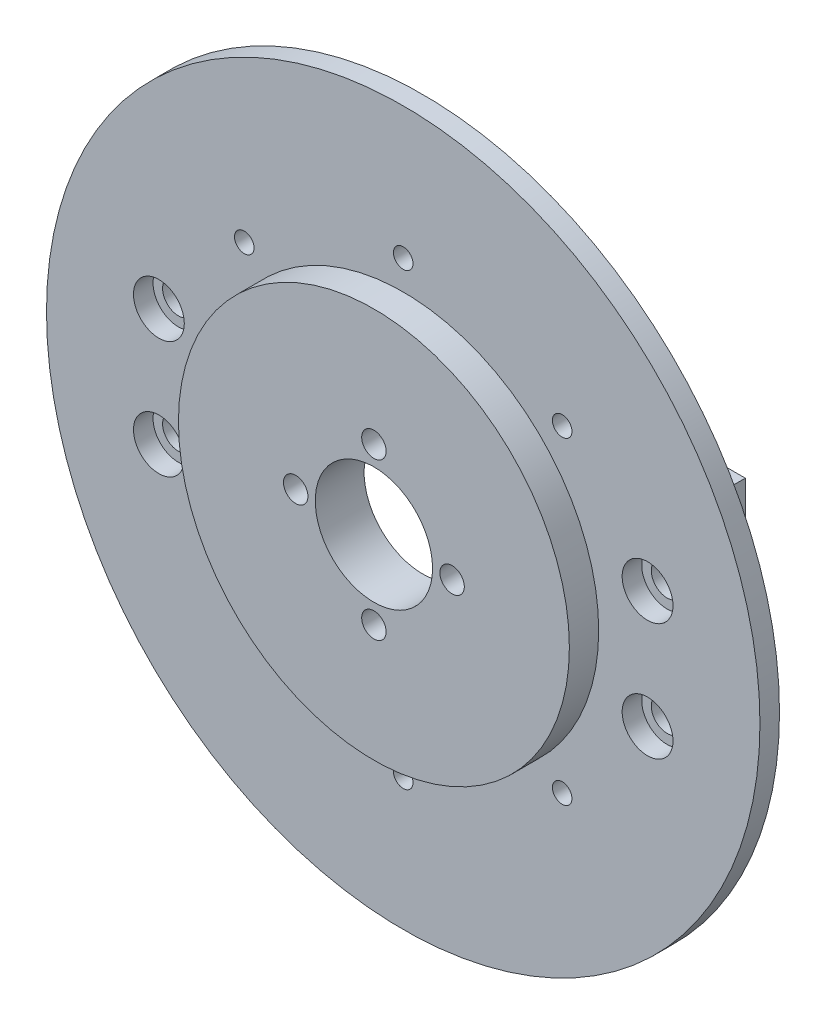
SolidWorks part; units mm, degrees
ref_plane "前视基准面" through (0, 0, 0) normal (0, 0, 1) x (1, 0, 0)
ref_plane "上视基准面" through (0, 0, 0) normal (0, 1, 0) x (1, 0, 0)
ref_plane "右视基准面" through (0, 0, 0) normal (1, 0, 0) x (0, 0, -1)
sketch "草图1" plane through (0, 0, 0) normal (0, 0, 1) x (1, 0, 0)
  line L1 (-74.8943, 22.0842) -> (-14.8943, 22.0842)
  line L2 (-74.8943, 22.0842) -> (-74.8943, -9.9158)
  line L3 (-74.8943, -9.9158) -> (-14.8943, -9.9158)
  line L4 (-14.8943, 22.0842) -> (-14.8943, -9.9158)
  dimension "D1" = 60
  dimension "D2" = 32
extrude "凸台-拉伸1" add sketch "草图1" along normal blind 3
sketch "草图3" plane through (0, 0, 3) normal (0, 0, 1) x (1, 0, 0)
  line L0 (-74.8943, 6.0842) -> (-14.8943, 6.0842) construction
  line L1 (-74.8943, 22.0842) -> (-74.8943, -9.9158) construction
  line L2 (-14.8943, -9.9158) -> (-14.8943, 22.0842) construction
  line L3 (-44.8943, 22.0842) -> (-44.8943, -9.9158) construction
  line L4 (-14.8943, 22.0842) -> (-74.8943, 22.0842) construction
  line L5 (-74.8943, -9.9158) -> (-14.8943, -9.9158) construction
  circle A0 centre (-44.8943, 6.0842) radius 36.5
  point P12 (-44.8943, 6.0842)
extrude "凸台-拉伸2" add sketch "草图3" along normal blind 2
sketch "草图4" plane through (0, 0, 5) normal (0, 0, 1) x (1, 0, 0)
  circle A0 centre (-44.8943, 29.0842) radius 1
  circle A2 centre (-44.8943, 6.0842) radius 36.5 construction
  dimension "D1" = 2
  dimension "D2" = 0
  dimension "D3" = 23
extrude "切除-拉伸2" cut sketch "草图4" against normal blind 10
pattern_circular "阵列(圆周)1" count 8 over 360 about axis through (-44.8943, 6.0842, 0) along (0, 0, 1) of "切除-拉伸2"
sketch "草图5" plane through (0, 0, 0) normal (0, 0, -1) x (-1, 0, 0)
  circle A0 centre (28.6308, 22.3477) radius 5
  circle A1 centre (61.1577, 22.3477) radius 5
  circle A2 centre (28.6308, -10.1792) radius 5
  circle A3 centre (61.1577, -10.1792) radius 5
extrude "切除-拉伸3" cut sketch "草图5" against normal blind 3
sketch "草图6" plane through (0, 0, 0) normal (0, 0, -1) x (-1, 0, 0)
  circle A0 centre (21.8943, 6.0842) radius 3
  circle A1 centre (67.8943, 6.0842) radius 3
extrude "凸台-拉伸3" add sketch "草图6" against normal blind 5
sketch "草图7" plane through (0, 0, 0) normal (0, 0, -1) x (-1, 0, 0)
  line L0 (14.8943, -9.9158) -> (14.8943, 22.0842) construction
  line L1 (14.8943, 22.0842) -> (23.6378, 22.0842) construction
  line L2 (23.6378, -9.9158) -> (14.8943, -9.9158) construction
  line L3 (66.1508, 22.0842) -> (74.8943, 22.0842) construction
  circle A0 centre (19.8943, 12.0842) radius 1.62
  circle A1 centre (19.8943, 0.0842) radius 1.62
  circle A2 centre (69.8943, 12.0842) radius 1.62
  circle A3 centre (69.8943, 0.0842) radius 1.62
  dimension "D1" = 3.24
  dimension "D2" = 5
  dimension "D3" = 10
  dimension "D4" = 3.24
  dimension "D5" = 10
  dimension "D6" = 5
  dimension "D7" = 3.24
  dimension "D8" = 50
  dimension "D9" = 10
  dimension "D10" = 3.24
  dimension "D11" = 0
  dimension "D12" = 50
extrude "切除-拉伸4" cut sketch "草图7" against normal blind 5
sketch "草图9" plane through (0, 0, 5) normal (0, 0, 1) x (1, 0, 0)
  circle A0 centre (-69.8943, 12.0842) radius 2.6
  circle A1 centre (-69.8943, 0.0842) radius 2.6
  circle A2 centre (-19.8943, 12.0842) radius 2.6
  circle A3 centre (-19.8943, 0.0842) radius 2.6
extrude "切除-拉伸5" cut sketch "草图9" against normal blind 2
sketch "草图10" plane through (0, 0, 5) normal (0, 0, 1) x (1, 0, 0)
  circle A0 centre (-44.8943, 6.0842) radius 20
extrude "凸台-拉伸4" add sketch "草图10" along normal blind 3
sketch "草图11" plane through (0, 0, 8) normal (0, 0, 1) x (1, 0, 0)
  circle A0 centre (-44.8943, 14.0842) radius 1.25
  circle A1 centre (-44.8943, 6.0842) radius 20 construction
  circle A2 centre (-44.8943, 6.0842) radius 20 construction
  dimension "D1" = 0
  dimension "D2" = 8
extrude "切除-拉伸6" cut sketch "草图11" against normal blind 10
pattern_circular "阵列(圆周)2" count 4 over 360 about axis through (-44.8943, 6.0842, 0) along (0, 0, 1) of "切除-拉伸6"
sketch "草图12" plane through (0, 0, 0) normal (0, 0, -1) x (-1, 0, 0)
  line L1 (23.6378, 22.0842) -> (66.1508, 22.0842)
  line L2 (23.6378, 22.0842) -> (23.6378, -9.9158)
  line L3 (23.6378, -9.9158) -> (66.1508, -9.9158)
  line L4 (66.1508, 22.0842) -> (66.1508, -9.9158)
extrude "切除-拉伸7" cut sketch "草图12" against normal blind 3
sketch "草图13" plane through (0, 0, 8) normal (0, 0, 1) x (1, 0, 0)
  circle A0 centre (-44.8943, 6.0842) radius 6
extrude "切除-拉伸8" cut sketch "草图13" against normal blind 10
